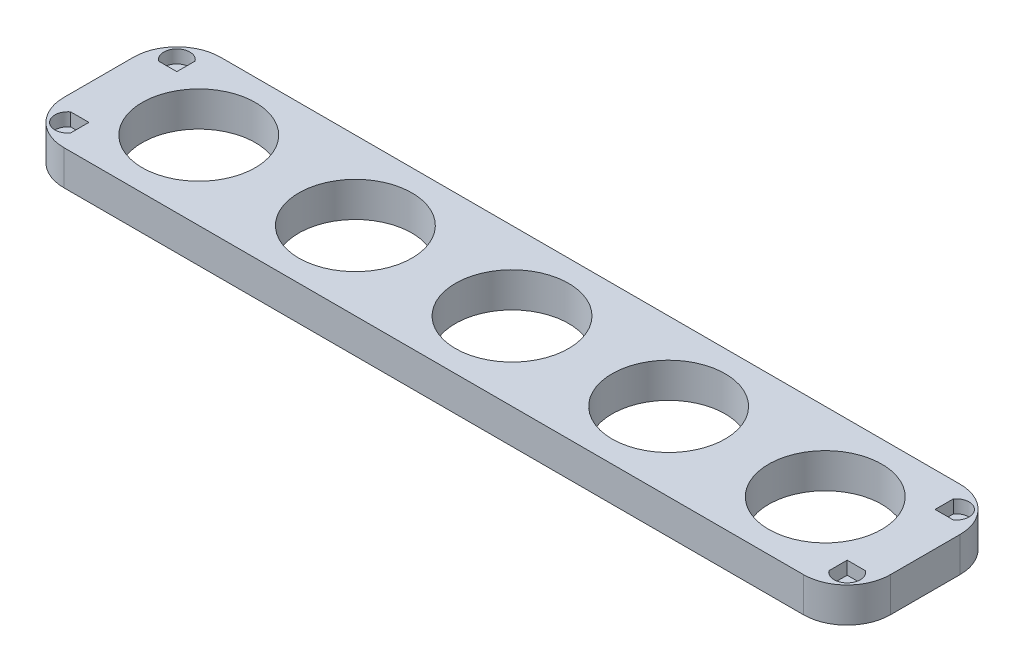
SolidWorks part; units mm, degrees
ref_plane "Front Plane" through (0, 0, 0) normal (0, 0, 1) x (1, 0, 0)
ref_plane "Top Plane" through (0, 0, 0) normal (0, 1, 0) x (1, 0, 0)
ref_plane "Right Plane" through (0, 0, 0) normal (1, 0, 0) x (0, 0, -1)
sketch "Sketch5" plane through (0, 0, 0) normal (0, 1, 0) x (1, 0, 0)
  line L1 (0, 0) -> (190, 0)
  line L2 (0, 0) -> (0, 36)
  line L3 (0, 36) -> (190, 36)
  line L4 (190, 0) -> (190, 36)
  dimension "D1" = 36
  dimension "D2" = 190
extrude "Boss-Extrude1" add sketch "Sketch5" along normal blind 8
sketch "Sketch6" plane through (0, 8, 0) normal (0, 1, 0) x (1, 0, 0)
  circle A0 centre (23, 18) radius 13
  circle A1 centre (59, 18) radius 13
  circle A2 centre (95.0046, 18) radius 13
  circle A3 centre (131.0046, 18) radius 13
  circle A4 centre (167.0023, 18) radius 12.9977
  point P6 (10, 18)
  point P7 (180, 18)
extrude "Cut-Extrude1" cut sketch "Sketch6" against normal blind 8
fillet "Fillet2" radius 10 4 edges at (190, 4, 0) (190, 4, -36) (0, 4, -36) (0, 4, 0)
sketch "Sketch7" plane through (0, 8, 0) normal (0, 1, 0) x (1, 0, 0)
  line L4 (0, 18) -> (190, 18)
  line L7 (3.6526, 28.1002) -> (7.8526, 28.1002)
  line L16 (7.8526, 28.1002) -> (7.8526, 32.3002)
  line L17 (0, 26) -> (0, 10) construction
  line L18 (190, 10) -> (190, 26) construction
  line L19 (95, 36) -> (95, 0)
  line L20 (180, 36) -> (10, 36) construction
  line L21 (10, 0) -> (180, 0) construction
  line L22 (10, 0) -> (9.8205, 7.9705)
  line L23 (0, 9.6137) -> (8, 9.5931)
  line L24 (3.6526, 7.8998) -> (7.8526, 7.8998)
  line L25 (7.8526, 7.8998) -> (7.8526, 3.6998)
  line L26 (0, 26.3863) -> (8, 26.4069)
  line L27 (10, 36) -> (9.8205, 28.0295)
  line L28 (180, 36) -> (180.1795, 28.0295)
  line L29 (190, 26.3863) -> (182, 26.4069)
  line L30 (186.3474, 28.1002) -> (182.1474, 28.1002)
  line L31 (182.1474, 28.1002) -> (182.1474, 32.3002)
  line L32 (190, 9.6137) -> (182, 9.5931)
  line L33 (180, 0) -> (180.1795, 7.9705)
  line L34 (182.1474, 7.8998) -> (182.1474, 3.6998)
  line L35 (186.3474, 7.8998) -> (182.1474, 7.8998)
  arc A12 (7.8526, 32.3002) -> (3.6526, 28.1002) centre (5.4465, 30.5062) ccw
  arc A14 (9.8205, 7.9705) -> (8, 9.5931) centre (10.0398, 10.0492) cw
  arc A15 (10, 0) -> (0, 9.6137) centre (10.0398, 10.0492) cw
  arc A16 (7.8526, 3.6998) -> (3.6526, 7.8998) centre (5.4465, 5.4938) cw
  arc A17 (9.8205, 28.0295) -> (8, 26.4069) centre (10.0398, 25.9508) ccw
  arc A18 (10, 36) -> (0, 26.3863) centre (10.0398, 25.9508) ccw
  arc A19 (180, 36) -> (190, 26.3863) centre (179.9602, 25.9508) cw
  arc A20 (180.1795, 28.0295) -> (182, 26.4069) centre (179.9602, 25.9508) cw
  arc A21 (182.1474, 32.3002) -> (186.3474, 28.1002) centre (184.5535, 30.5062) cw
  arc A22 (180, 0) -> (190, 9.6137) centre (179.9602, 10.0492) ccw
  arc A23 (180.1795, 7.9705) -> (182, 9.5931) centre (179.9602, 10.0492) ccw
  arc A24 (182.1474, 3.6998) -> (186.3474, 7.8998) centre (184.5535, 5.4938) ccw
  point P23 (10, 0)
  point P24 (0, 9.593)
extrude "Cut-Extrude2" cut sketch "Sketch7" against normal blind 3 contours L16 A12 L7 | L24 L25 A16 | L30 L31 A21 | A24 L35 L34
